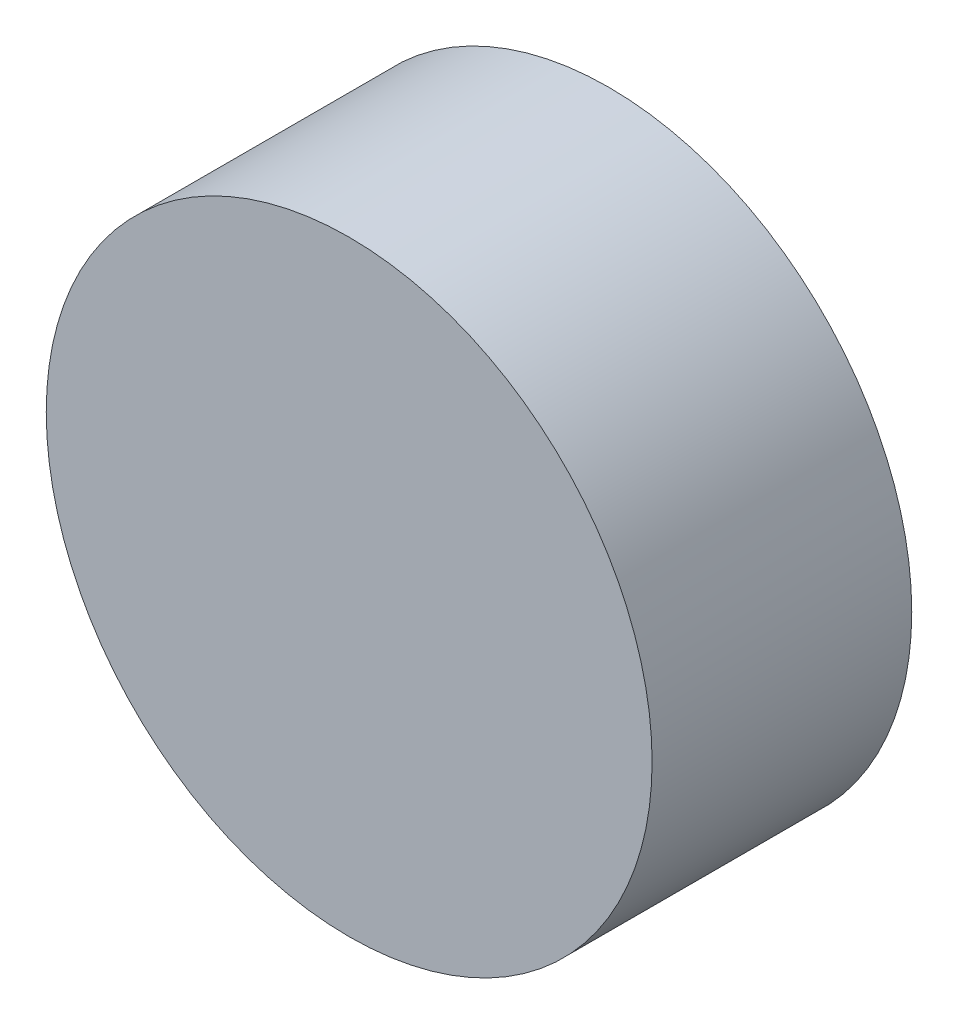
SolidWorks part; units mm, degrees
ref_plane "Front Plane" through (0, 0, 0) normal (0, 0, 1) x (1, 0, 0)
ref_plane "Top Plane" through (0, 0, 0) normal (0, 1, 0) x (1, 0, 0)
ref_plane "Right Plane" through (0, 0, 0) normal (1, 0, 0) x (0, 0, -1)
sketch "Sketch2" plane through (0, 0, 0) normal (0, 0, 1) x (1, 0, 0)
  circle A0 centre (0, 0) radius 3.5
  dimension "D1" = 7
extrude "Boss-Extrude1" add sketch "Sketch2" along normal blind 3
